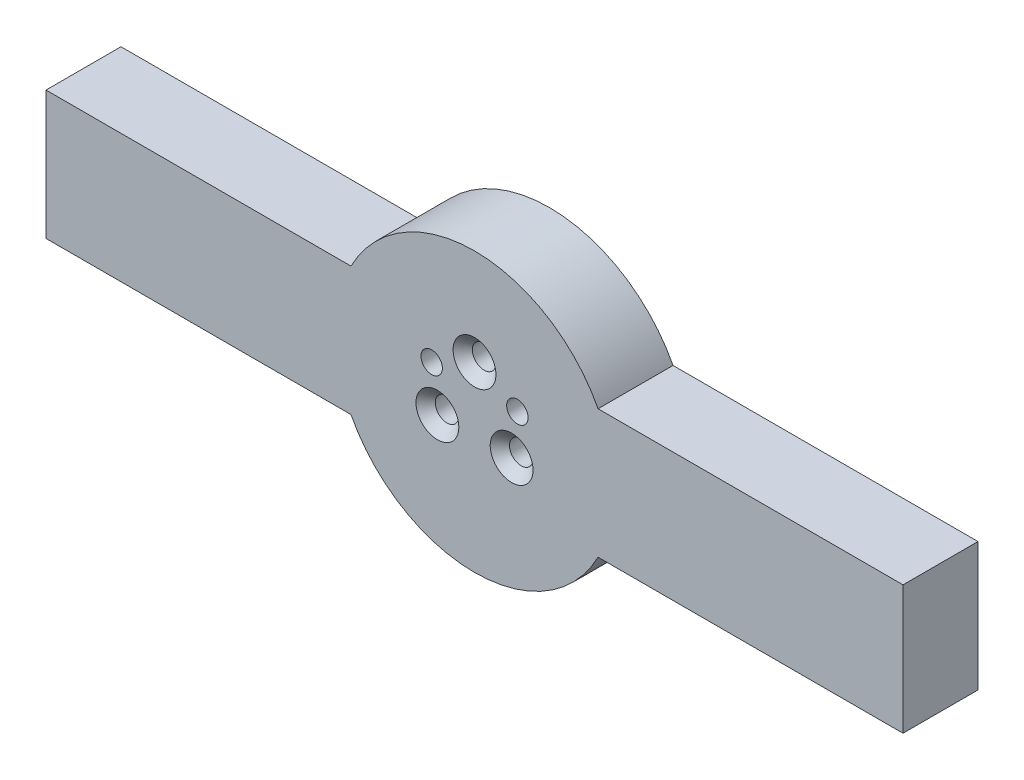
SolidWorks part; units mm, degrees
ref_plane "Plano frontal" through (0, 0, 0) normal (0, 0, 1) x (1, 0, 0)
ref_plane "Plano superior" through (0, 0, 0) normal (0, 1, 0) x (1, 0, 0)
ref_plane "Plano direito" through (0, 0, 0) normal (1, 0, 0) x (0, 0, -1)
sketch "Esboço1" plane through (0, 0, 0) normal (0, 0, 1) x (1, 0, 0)
  line L0 (-200, -240) -> (-200, 0) construction
  line L1 (200, -240) -> (35, -240) construction
  line L11 (-200, -270) -> (-57.6628, -270)
  line L12 (200, -270) -> (200, -210)
  line L13 (200, -210) -> (57.6628, -210)
  line L14 (-200, -210) -> (-200, -270)
  line L18 (57.6628, -270) -> (200, -270)
  line L19 (-57.6628, -210) -> (-200, -210)
  arc A1 (57.6628, -210) -> (-57.6628, -210) centre (0, -240) ccw
  arc A2 (-57.6628, -270) -> (57.6628, -270) centre (0, -240) ccw
  dimension "D1" = 200
  dimension "D3" = 0
  dimension "D6" = 65
  dimension "D2" = 400
  dimension "D4" = 60
  dimension "D5" = 30
extrude "Ressalto-extrusão1" add sketch "Esboço1" along normal blind 35
sketch "Esboço2" plane through (0, 0, 0) normal (0, 0, -1) x (-1, 0, 0)
  circle A0 centre (0, -240) radius 35
  arc A2 (-57.6628, -270) -> (57.6628, -270) centre (0, -240) ccw construction
  dimension "D1" = 70
sketch "Esboço3" plane through (0, 0, 0) normal (0, 0, -1) x (-1, 0, 0)
  circle A0 centre (0, -240) radius 35
  arc A2 (-57.6628, -270) -> (57.6628, -270) centre (0, -240) ccw construction
extrude "Corte-extrusão2" cut sketch "Esboço3" against normal blind 15
hole_wizard "Escareado para parafuso com cabeça escareada elevada de M101" positions "Esboço4" profile "Esboço5" countersink size "M10" standard "DIN" end condition through all
sketch "Esboço4" plane through (0, 0, 35) normal (0, 0, 1) x (1, 0, 0)
  line L0 (0, -247.5522) -> (0, -202.2544) construction
  line L2 (0, -240) -> (-34.0957, -259.6852) construction
  line L4 (0, -240) -> (36.5091, -261.0785) construction
  circle A0 centre (0, -240) radius 35 construction
  circle A1 centre (0, -240) radius 35
  point P0 (0, -220)
  point P2 (-17.3205, -250)
  point P4 (17.3205, -250)
  dimension "D1" = 20
  dimension "D2" = 20
  dimension "D3" = 20
  dimension "D4" = 120
  dimension "D5" = 120
sketch "Esboço5" plane through (0, -220, 35) normal (1, 0, 0) x (0, -1, 0)
  line L0 (0, 0) -> (0, 35)
  line L1 (0, 35) -> (5.5, 35)
  line L2 (5.5, 35) -> (5.5, 4.5)
  line L3 (5.5, 4.5) -> (10, 0)
  line L5 (10, 0) -> (0, 0)
  line L6 (-5.5, 4.5) -> (-10, 0) construction
  line L11 (0, -6.35) -> (0, 107.95) construction
  dimension "Thru Hole Dia." = 11
  dimension "Thru Hole Depth" = 35
  dimension "Near C'Sink Dia." = 20
  dimension "Near C'Sink Angle" = 90
hole_wizard "Furos-guia com Ø10.0mm1" positions "Esboço6" profile "Esboço7" hole size "Ø10.0" standard "DIN" end condition through all
sketch "Esboço6" plane through (0, 0, 35) normal (0, 0, 1) x (1, 0, 0)
  circle A0 centre (0, -240) radius 35 construction
  circle A1 centre (0, -240) radius 35
  point P0 (-20, -230)
  point P2 (20, -230)
  dimension "D1" = 10
  dimension "D2" = 10
  dimension "D3" = 20
  dimension "D4" = 20
sketch "Esboço7" plane through (-20, -230, 35) normal (1, 0, 0) x (0, -1, 0)
  line L0 (0, 0) -> (0, 35)
  line L1 (0, 35) -> (5, 35)
  line L2 (5, 35) -> (5, 0)
  line L5 (5, 0) -> (0, 0)
  line L11 (0, -6.35) -> (0, 107.95) construction
  dimension "Thru Hole Dia." = 10
  dimension "Thru Hole Depth" = 35
extrude "Corte-extrusão1" cut sketch "Esboço2" against normal blind 15
